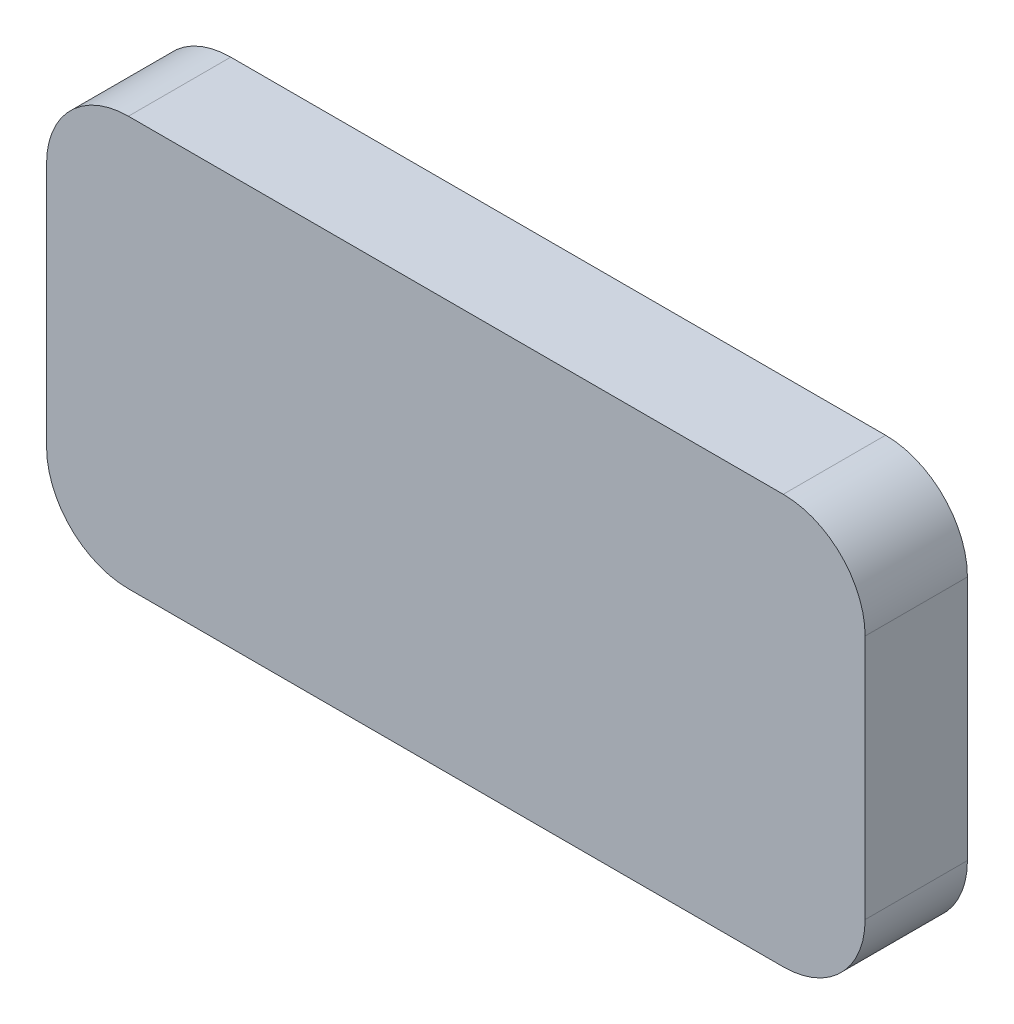
SolidWorks part; units mm, degrees
ref_plane "Спереди" through (0, 0, 0) normal (0, 0, 1) x (1, 0, 0)
ref_plane "Сверху" through (0, 0, 0) normal (0, 1, 0) x (1, 0, 0)
ref_plane "Справа" through (0, 0, 0) normal (1, 0, 0) x (0, 0, -1)
sketch "Эскиз1" plane through (0, 0, 0) normal (0, 0, 1) x (1, 0, 0)
  line L1 (-16, -10) -> (16, -10)
  line L2 (-20, -6) -> (-20, 6)
  line L3 (-16, 10) -> (16, 10)
  line L4 (20, -6) -> (20, 6)
  line L5 (-20, -10) -> (20, 10) construction
  line L6 (-20, 10) -> (20, -10) construction
  arc A0 (16, 10) -> (20, 6) centre (16, 6) cw
  arc A1 (16, -10) -> (20, -6) centre (16, -6) ccw
  arc A2 (-16, -10) -> (-20, -6) centre (-16, -6) cw
  arc A3 (-20, 6) -> (-16, 10) centre (-16, 6) cw
  point P0 (0, 0)
  dimension "D3" = 4
  dimension "D1" = 40
  dimension "D2" = 20
extrude "Бобышка-Вытянуть1" add sketch "Эскиз1" along normal blind 5
